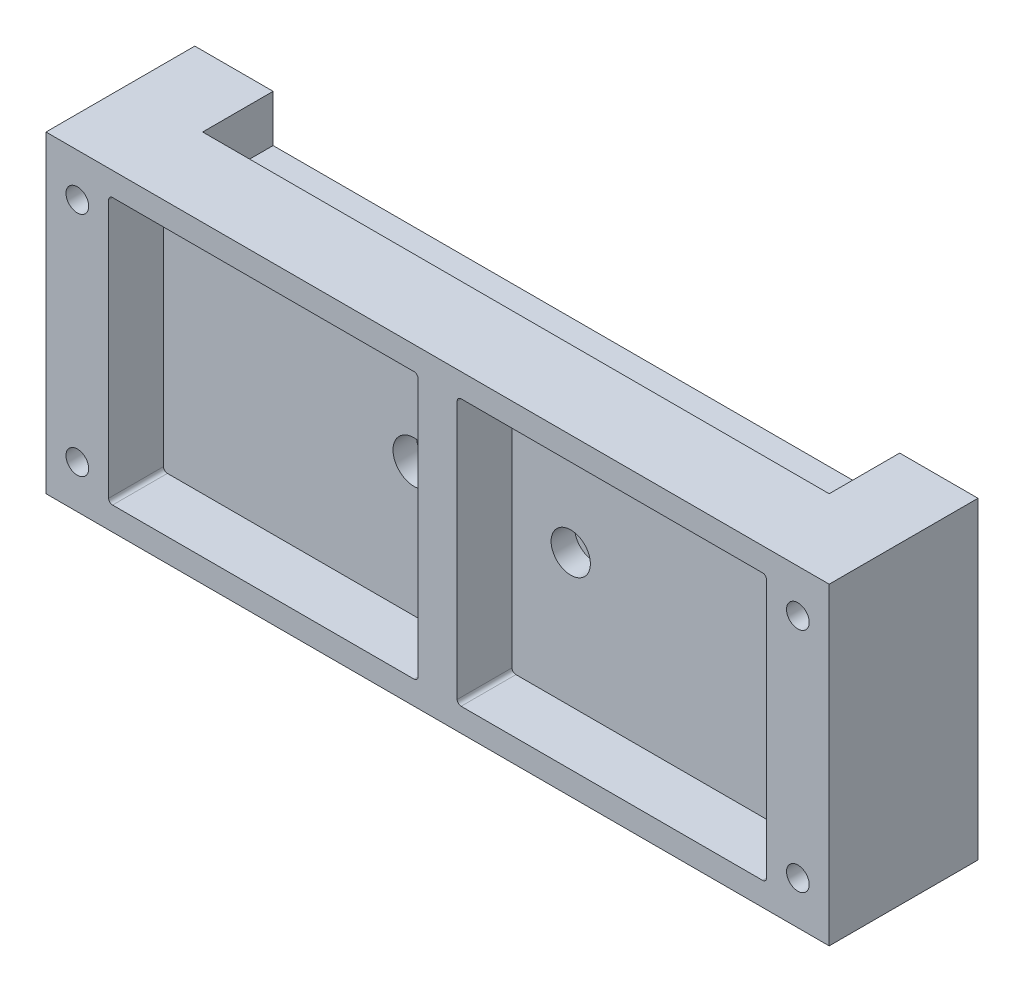
SolidWorks part; units mm, degrees
ref_plane "Front Plane" through (0, 0, 0) normal (0, 0, 1) x (1, 0, 0)
ref_plane "Top Plane" through (0, 0, 0) normal (0, 1, 0) x (1, 0, 0)
ref_plane "Right Plane" through (0, 0, 0) normal (1, 0, 0) x (0, 0, -1)
sketch "Sketch1" plane through (0, 0, 0) normal (0, 0, 1) x (1, 0, 0)
  line L1 (-33.75, 21.5625) -> (66.25, 21.5625)
  line L2 (-33.75, 21.5625) -> (-33.75, -18.4375)
  line L3 (-33.75, -18.4375) -> (66.25, -18.4375)
  line L4 (66.25, 21.5625) -> (66.25, -18.4375)
  dimension "D1" = 100
  dimension "D2" = 40
extrude "Boss-Extrude1" add sketch "Sketch1" along normal blind 38
sketch "Sketch2" plane through (0, 0, 0) normal (0, 0, -1) x (-1, 0, 0)
  line L0 (-66.25, -18.4375) -> (-66.25, 21.5625) construction
  line L1 (-58.25, 18.5625) -> (-18.75, 18.5625)
  line L2 (-58.25, 18.5625) -> (-58.25, -15.4375)
  line L3 (-58.25, -15.4375) -> (-18.75, -15.4375)
  line L4 (-18.75, 18.5625) -> (-18.75, -15.4375)
  line L5 (-13.75, 18.5625) -> (25.75, 18.5625)
  line L6 (-13.75, 18.5625) -> (-13.75, -15.4375)
  line L7 (-13.75, -15.4375) -> (25.75, -15.4375)
  line L8 (25.75, 18.5625) -> (25.75, -15.4375)
  line L9 (33.75, 21.5625) -> (33.75, -18.4375) construction
  line L10 (-66.25, 21.5625) -> (33.75, 21.5625) construction
  line L11 (33.75, -18.4375) -> (-66.25, -18.4375) construction
  dimension "D1" = 8
  dimension "D2" = 8
  dimension "D3" = 5
  dimension "D4" = 3
  dimension "D5" = 3
  dimension "D6" = 3
  dimension "D7" = 3
  dimension "D8" = 39.5
  dimension "D9" = 39.5
extrude "Cut-Extrude2" cut sketch "Sketch2" against normal blind 21 from offset 12 offset against normal yes
sketch "Sketch4" plane through (0, 0, 0) normal (0, 0, -1) x (-1, 0, 0)
  line L0 (-66.25, -18.4375) -> (-66.25, 21.5625) construction
  line L1 (33.75, 21.5625) -> (33.75, -18.4375) construction
  line L2 (-66.25, 21.5625) -> (33.75, 21.5625) construction
  line L3 (33.75, -18.4375) -> (-66.25, -18.4375) construction
  circle A0 centre (-62.25, 16.0625) radius 1.45
  circle A1 centre (-62.25, -12.9375) radius 1.45
  circle A2 centre (29.75, 16.0625) radius 1.45
  circle A3 centre (29.75, -12.9375) radius 1.45
  dimension "D1" = 4
  dimension "D2" = 4
  dimension "D3" = 5.5
  dimension "D4" = 5.5
extrude "Cut-Extrude4" cut sketch "Sketch4" against normal up to next
sketch "Sketch6" plane through (0, 21.5625, 0) normal (0, 1, 0) x (1, 0, 0)
  line L0 (-33.75, -38) -> (-33.75, 0) construction
  line L1 (66.25, -38) -> (-33.75, -38)
  line L2 (66.25, -38) -> (66.25, -19)
  line L3 (66.25, -19) -> (-33.75, -19)
  line L4 (-33.75, -38) -> (-33.75, -19)
extrude "Cut-Extrude5" cut sketch "Sketch6" against normal through all
fillet "Fillet1" radius 0.5 8 edges at (58.25, 18.5625, 15.5) (58.25, -15.4375, 15.5) (18.75, -15.4375, 15.5) (18.75, 18.5625, 15.5) (13.75, 18.5625, 15.5) (13.75, -15.4375, 15.5) (-25.75, -15.4375, 15.5) (-25.75, 18.5625, 15.5)
sketch "Sketch10" plane through (0, 0, 12) normal (0, 0, 1) x (1, 0, 0)
  line L8 (14.25, -14.9375) -> (14.25, 18.0625)
  line L9 (13.25, 19.0625) -> (-25.25, 19.0625)
  line L10 (-26.25, 18.0625) -> (-26.25, -14.9375)
  line L11 (-25.25, -15.9375) -> (13.25, -15.9375)
  line L12 (14.25, -14.9375) -> (14.25, 18.0625)
  line L13 (13.25, 19.0625) -> (-25.25, 19.0625)
  line L14 (-26.25, 18.0625) -> (-26.25, -14.9375)
  line L15 (-25.25, -15.9375) -> (13.25, -15.9375)
  arc A8 (14.25, 18.0625) -> (13.25, 19.0625) centre (13.25, 18.0625) ccw
  arc A9 (-25.25, 19.0625) -> (-26.25, 18.0625) centre (-25.25, 18.0625) ccw
  arc A10 (-26.25, -14.9375) -> (-25.25, -15.9375) centre (-25.25, -14.9375) ccw
  arc A11 (13.25, -15.9375) -> (14.25, -14.9375) centre (13.25, -14.9375) ccw
  arc A12 (14.25, 18.0625) -> (13.25, 19.0625) centre (13.25, 18.0625) ccw
  arc A13 (-25.25, 19.0625) -> (-26.25, 18.0625) centre (-25.25, 18.0625) ccw
  arc A14 (-26.25, -14.9375) -> (-25.25, -15.9375) centre (-25.25, -14.9375) ccw
  arc A15 (13.25, -15.9375) -> (14.25, -14.9375) centre (13.25, -14.9375) ccw
  dimension "D1" = 0.5
sketch "Sketch11" plane through (0, 0, 12) normal (0, 0, 1) x (1, 0, 0)
  line L8 (58.75, -14.9375) -> (58.75, 18.0625)
  line L9 (57.75, 19.0625) -> (19.25, 19.0625)
  line L10 (18.25, 18.0625) -> (18.25, -14.9375)
  line L11 (19.25, -15.9375) -> (57.75, -15.9375)
  line L12 (58.75, -14.9375) -> (58.75, 18.0625)
  line L13 (57.75, 19.0625) -> (19.25, 19.0625)
  line L14 (18.25, 18.0625) -> (18.25, -14.9375)
  line L15 (19.25, -15.9375) -> (57.75, -15.9375)
  arc A8 (58.75, 18.0625) -> (57.75, 19.0625) centre (57.75, 18.0625) ccw
  arc A9 (19.25, 19.0625) -> (18.25, 18.0625) centre (19.25, 18.0625) ccw
  arc A10 (18.25, -14.9375) -> (19.25, -15.9375) centre (19.25, -14.9375) ccw
  arc A11 (57.75, -15.9375) -> (58.75, -14.9375) centre (57.75, -14.9375) ccw
  arc A12 (58.75, 18.0625) -> (57.75, 19.0625) centre (57.75, 18.0625) ccw
  arc A13 (19.25, 19.0625) -> (18.25, 18.0625) centre (19.25, 18.0625) ccw
  arc A14 (18.25, -14.9375) -> (19.25, -15.9375) centre (19.25, -14.9375) ccw
  arc A15 (57.75, -15.9375) -> (58.75, -14.9375) centre (57.75, -14.9375) ccw
  dimension "D1" = 0.5
sketch "Sketch17" plane through (0, 0, 0) normal (0, 0, -1) x (-1, 0, 0)
  line L0 (-66.25, 1.5625) -> (33.75, 1.5625) construction
  line L3 (-16.25, 21.5625) -> (-16.25, -18.4375) construction
  line L4 (-66.25, 21.5625) -> (33.75, 21.5625) construction
  line L5 (33.75, -18.4375) -> (-66.25, -18.4375) construction
  line L6 (-66.25, -18.4375) -> (-66.25, 21.5625) construction
  line L9 (33.75, 21.5625) -> (33.75, -18.4375) construction
  line L10 (-56.25, 1.5625) -> (23.75, 1.5625) construction
  line L11 (-56.25, 9.0625) -> (23.75, 9.0625)
  line L12 (-56.25, -5.9375) -> (23.75, -5.9375)
  arc A2 (-56.25, 9.0625) -> (-56.25, -5.9375) centre (-56.25, 1.5625) ccw
  arc A3 (23.75, -5.9375) -> (23.75, 9.0625) centre (23.75, 1.5625) ccw
  point P15 (-16.25, 1.5625)
extrude "Cut-Extrude12" cut sketch "Sketch17" against normal blind 9
sketch "Sketch18" plane through (0, 0, 9) normal (0, 0, -1) x (-1, 0, 0)
  line L0 (-66.25, 1.5625) -> (33.75, 1.5625) construction
  line L1 (-66.25, -18.4375) -> (-66.25, 21.5625) construction
  line L2 (33.75, 21.5625) -> (33.75, -18.4375) construction
  line L3 (-16.25, 21.5625) -> (-16.25, -18.4375) construction
  line L4 (-66.25, 21.5625) -> (33.75, 21.5625) construction
  line L5 (33.75, -18.4375) -> (-66.25, -18.4375) construction
  circle A0 centre (-26.25, 1.5625) radius 2.5069
  circle A1 centre (-6.25, 1.5625) radius 2.6931
  dimension "D1" = 20
  dimension "D2" = 10
  dimension "D3" = 10
extrude "Cut-Extrude13" cut sketch "Sketch18" against normal up to next
sketch "Sketch19" plane through (0, 0, 9) normal (0, 0, -1) x (-1, 0, 0)
  circle A0 centre (-26.25, 1.5625) radius 4.572
  circle A1 centre (-26.25, 1.5625) radius 6.477
  circle A2 centre (-6.25, 1.5625) radius 4.572
  circle A3 centre (-6.25, 1.5625) radius 6.477
  dimension "D1" = 9.144
  dimension "D2" = 12.954
  dimension "D3" = 12.954
  dimension "D4" = 9.144
extrude "Cut-Extrude14" cut sketch "Sketch19" against normal blind 0.7937 contours A1 A0 | A3 A2
sketch "Sketch20" plane through (-33.75, 0, 0) normal (-1, 0, 0) x (0, 0, 1)
  line L0 (0, 12.0625) -> (-2, 12.0625)
  line L1 (0, 21.5625) -> (0, -18.4375) construction
  line L2 (-2, 12.0625) -> (-2, 9.0625)
  line L8 (9, 9.0625) -> (9, -5.9375) construction
  line L9 (9, 1.5625) -> (-12.0371, 1.5625) construction
  line L10 (-2, -8.9375) -> (-2, -5.9375)
  line L15 (0, -8.9375) -> (-2, -8.9375)
  line L16 (-2, 9.0625) -> (0, 9.0625)
  line L17 (0, 9.0625) -> (0, 12.0625)
  line L18 (-2, -5.9375) -> (0, -5.9375)
  line L19 (0, -5.9375) -> (0, -8.9375)
  dimension "D4" = 3
  dimension "D5" = 2
sketch "Sketch21" plane through (0, 0, 0) normal (0, 0, -1) x (-1, 0, 0)
  line L0 (33.75, 21.5625) -> (33.75, -18.4375) construction
  line L1 (23.75, 9.0625) -> (33.75, 9.0625)
  line L2 (23.75, 9.0625) -> (23.75, -5.9375)
  line L3 (23.75, -5.9375) -> (33.75, -5.9375)
  line L4 (33.75, 9.0625) -> (33.75, -5.9375)
extrude "Cut-Extrude15" cut sketch "Sketch21" against normal up to surface (9 mm away) up to face at (19.773, 1.5625, 9)
sketch "Sketch22" plane through (-33.75, 0, 0) normal (-1, 0, 0) x (0, 0, 1)
  line L0 (9, 1.5625) -> (-10.0634, 1.5625) construction
  line L1 (9, 9.0625) -> (9, -5.9375) construction
  line L2 (9, 9.0625) -> (0, 9.0625) construction
  line L3 (2, 9.0625) -> (6, 9.0625)
  line L4 (2, 9.0625) -> (2, 11.5625)
  line L5 (2, 11.5625) -> (6, 11.5625)
  line L6 (6, 9.0625) -> (6, 11.5625)
  line L7 (2, -5.9375) -> (2, -8.4375)
  line L8 (2, -5.9375) -> (6, -5.9375)
  line L9 (6, -5.9375) -> (6, -8.4375)
  line L10 (2, -8.4375) -> (6, -8.4375)
  line L11 (0, 21.5625) -> (0, 9.0625) construction
  dimension "D1" = 4
  dimension "D2" = 2.5
  dimension "D3" = 2
extrude "Cut-Extrude16" cut sketch "Sketch22" against normal blind 90
sketch "Sketch23" plane through (0, 0, 0) normal (0, 0, -1) x (-1, 0, 0)
  line L0 (-63.75, 1.5625) -> (37.5576, 1.5625) construction
  line L1 (-66.25, 21.5625) -> (33.75, 21.5625) construction
  line L2 (-56.25, 21.5625) -> (23.75, 21.5625)
  line L3 (-56.25, 21.5625) -> (-56.25, 15.5625)
  line L4 (-56.25, 15.5625) -> (23.75, 15.5625)
  line L5 (23.75, 21.5625) -> (23.75, 15.5625)
  line L6 (-56.25, -18.4375) -> (-56.25, -12.4375)
  line L7 (-56.25, -18.4375) -> (23.75, -18.4375)
  line L8 (23.75, -18.4375) -> (23.75, -12.4375)
  line L9 (-56.25, -12.4375) -> (23.75, -12.4375)
  line L10 (33.75, 21.5625) -> (33.75, 9.0625) construction
  arc A0 (-56.25, 9.0625) -> (-56.25, -5.9375) centre (-56.25, 1.5625) ccw construction
  dimension "D1" = 80
  dimension "D2" = 10
  dimension "D3" = 6
extrude "Cut-Extrude17" cut sketch "Sketch23" against normal blind 9
